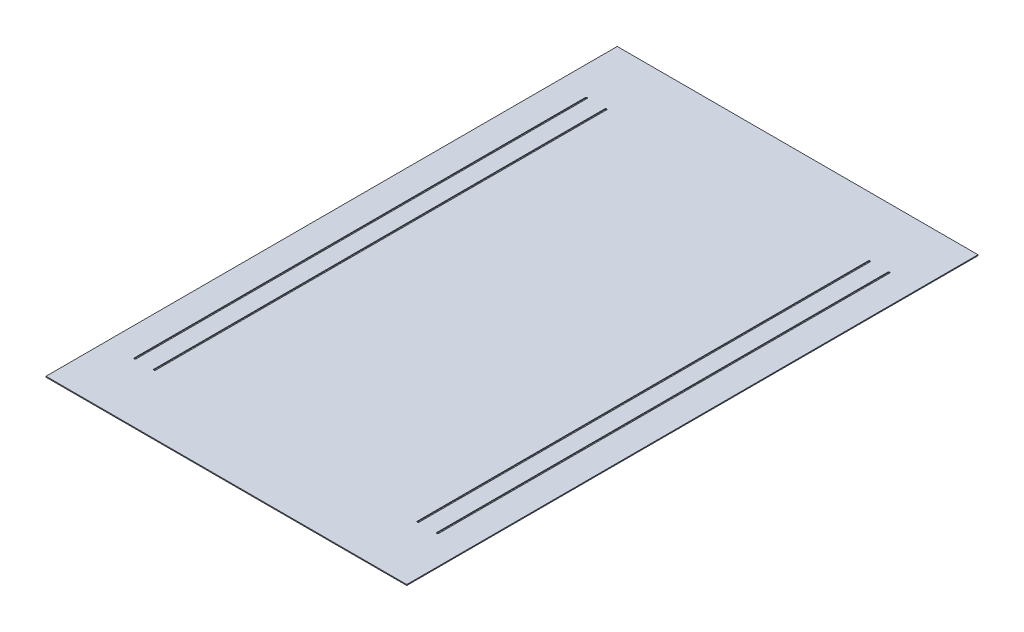
SolidWorks part; units mm, degrees
ref_plane "Front Plane" through (0, 0, 0) normal (0, 0, 1) x (1, 0, 0)
ref_plane "Top Plane" through (0, 0, 0) normal (0, 1, 0) x (1, 0, 0)
ref_plane "Right Plane" through (0, 0, 0) normal (1, 0, 0) x (0, 0, -1)
sketch "Sketch1" plane through (0, 0, 0) normal (0, 1, 0) x (1, 0, 0)
  line L0 (-503, 750) -> (-503, -750) construction
  line L1 (-600, 950) -> (600, 950)
  line L2 (-600, 950) -> (-600, -950)
  line L3 (-600, -950) -> (600, -950)
  line L4 (600, 950) -> (600, -950)
  line L5 (-500, 750) -> (-500, -750)
  line L6 (-506, 750) -> (-506, -750)
  line L7 (-438, 750) -> (-438, -750) construction
  line L8 (-435, 750) -> (-435, -750)
  line L9 (-441, 750) -> (-441, -750)
  line L10 (0, 665.803) -> (0, -634.197) construction
  line L11 (438, 750) -> (438, -750) construction
  line L12 (435, 750) -> (435, -750)
  line L13 (441, 750) -> (441, -750)
  line L14 (503, 750) -> (503, -750) construction
  line L15 (500, 750) -> (500, -750)
  line L16 (506, 750) -> (506, -750)
  arc A0 (-500, 750) -> (-506, 750) centre (-503, 750) ccw
  arc A1 (-506, -750) -> (-500, -750) centre (-503, -750) ccw
  arc A2 (-435, 750) -> (-441, 750) centre (-438, 750) ccw
  arc A3 (-441, -750) -> (-435, -750) centre (-438, -750) ccw
  arc A4 (435, 750) -> (441, 750) centre (438, 750) cw
  arc A5 (441, -750) -> (435, -750) centre (438, -750) cw
  arc A6 (500, 750) -> (506, 750) centre (503, 750) cw
  arc A7 (506, -750) -> (500, -750) centre (503, -750) cw
  point P7 (-503, 0)
  point P15 (-438, 0)
  point P23 (438, 0)
  point P30 (503, 0)
  dimension "D6" = 3
  dimension "D10" = 3
  dimension "D1" = 1200
  dimension "D2" = 1900
  dimension "D3" = 600
  dimension "D4" = 950
  dimension "D5" = 1500
  dimension "D7" = 750
  dimension "D8" = 750
  dimension "D9" = 500
  dimension "D11" = 435
extrude "Boss-Extrude1" add sketch "Sketch1" along normal blind 3
